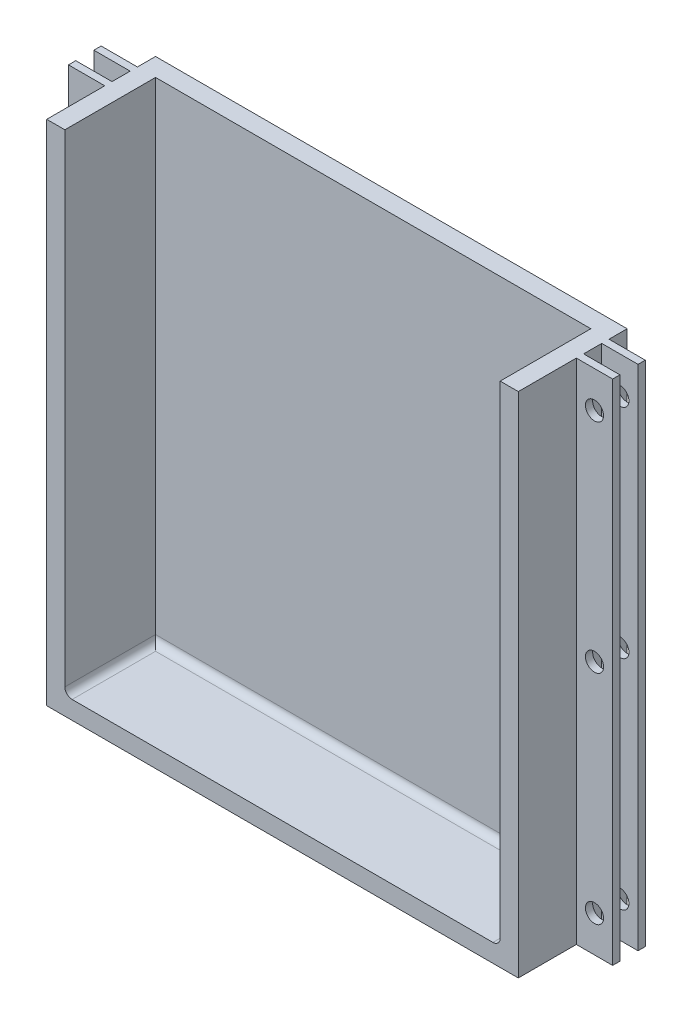
SolidWorks part; units mm, degrees
ref_plane "Front Plane" through (0, 0, 0) normal (0, 0, 1) x (1, 0, 0)
ref_plane "Top Plane" through (0, 0, 0) normal (0, 1, 0) x (1, 0, 0)
ref_plane "Right Plane" through (0, 0, 0) normal (1, 0, 0) x (0, 0, -1)
sketch "Sketch1" plane through (0, 0, 0) normal (0, 1, 0) x (1, 0, 0)
  line L0 (-82.55, 0) -> (82.55, 0) construction
  line L1 (76.2, 0) -> (82.55, 0)
  line L2 (-82.55, 0) -> (-76.2, 0)
  line L3 (-82.55, 0) -> (-82.55, 38.1)
  line L4 (-82.55, 38.1) -> (82.55, 38.1)
  line L5 (82.55, 0) -> (82.55, 38.1)
  line L7 (-76.2, 0) -> (-76.2, 31.75)
  line L8 (-76.2, 31.75) -> (76.2, 31.75)
  line L9 (76.2, 0) -> (76.2, 31.75)
  point P3 (0, 0)
  dimension "D1" = 165.1
  dimension "D2" = 38.1
  dimension "D3" = 6.35
  dimension "D4" = 6.35
  dimension "D5" = 6.35
extrude "Boss-Extrude1" add sketch "Sketch1" along normal blind 177.8 contours L4 L5 L1 L9 L8 L7 L2 L3
sketch "Sketch2" plane through (0, 177.8, 0) normal (0, 1, 0) x (1, 0, 0)
  line L0 (82.55, 0) -> (82.55, 38.1) construction
  line L1 (82.55, 31.75) -> (95.25, 31.75)
  line L2 (82.55, 31.75) -> (82.55, 29.21)
  line L3 (82.55, 29.21) -> (95.25, 29.21)
  line L4 (95.25, 31.75) -> (95.25, 29.21)
  line L5 (-82.55, 38.1) -> (82.55, 38.1) construction
  line L6 (82.55, 22.86) -> (95.25, 22.86)
  line L7 (82.55, 22.86) -> (82.55, 20.32)
  line L8 (82.55, 20.32) -> (95.25, 20.32)
  line L9 (95.25, 22.86) -> (95.25, 20.32)
  line L10 (0, 0) -> (0, 38.1) construction
  line L11 (-95.25, 22.86) -> (-95.25, 20.32)
  line L12 (-82.55, 20.32) -> (-95.25, 20.32)
  line L13 (-82.55, 22.86) -> (-82.55, 20.32)
  line L14 (-82.55, 22.86) -> (-95.25, 22.86)
  line L15 (-95.25, 31.75) -> (-95.25, 29.21)
  line L16 (-82.55, 29.21) -> (-95.25, 29.21)
  line L17 (-82.55, 31.75) -> (-82.55, 29.21)
  line L18 (-82.55, 31.75) -> (-95.25, 31.75)
  dimension "D1" = 6.35
  dimension "D2" = 2.54
  dimension "D3" = 12.7
  dimension "D4" = 6.35
extrude "Boss-Extrude2" add sketch "Sketch2" against normal up to surface (177.8 mm away) up to face at (0, 0, -17.4625)
sketch "Sketch3" plane through (0, 0, -20.32) normal (0, 0, 1) x (1, 0, 0)
  line L0 (88.9, 0) -> (88.9, 177.8) construction
  line L1 (82.55, 0) -> (95.25, 0) construction
  line L2 (82.55, 177.8) -> (95.25, 177.8) construction
  line L3 (0, 0) -> (0, 177.8) construction
  line L4 (-76.2, 177.8) -> (76.2, 177.8) construction
  circle A0 centre (88.9, 12.7) radius 3.175
  circle A1 centre (88.9, 88.9) radius 3.175
  circle A2 centre (88.9, 165.1) radius 3.175
  circle A3 centre (-88.9, 12.7) radius 3.175
  circle A4 centre (-88.9, 165.1) radius 3.175
  circle A5 centre (-88.9, 88.9) radius 3.175
  dimension "D1" = 6.35
  dimension "D2" = 12.7
  dimension "D4" = 76.2
  dimension "D3" = 3
extrude "Cut-Extrude1" cut sketch "Sketch3" against normal through all
sketch "Sketch4" plane through (-76.2, 0, 0) normal (1, 0, 0) x (0, 0, -1)
  line L0 (31.75, 0) -> (31.75, 177.8) construction
  line L1 (0, 0) -> (31.75, 0)
  line L2 (0, 0) -> (0, 6.35)
  line L3 (0, 6.35) -> (31.75, 6.35)
  line L4 (31.75, 0) -> (31.75, 6.35)
  dimension "D1" = 6.35
extrude "Boss-Extrude3" add sketch "Sketch4" along normal up to surface (152.4 mm away) up to face at (76.2, 88.9, -15.875)
fillet "Fillet1" radius 2.54 3 edges at (76.2, 6.35, -15.875) (-76.2, 6.35, -15.875) (0, 6.35, -31.75)
